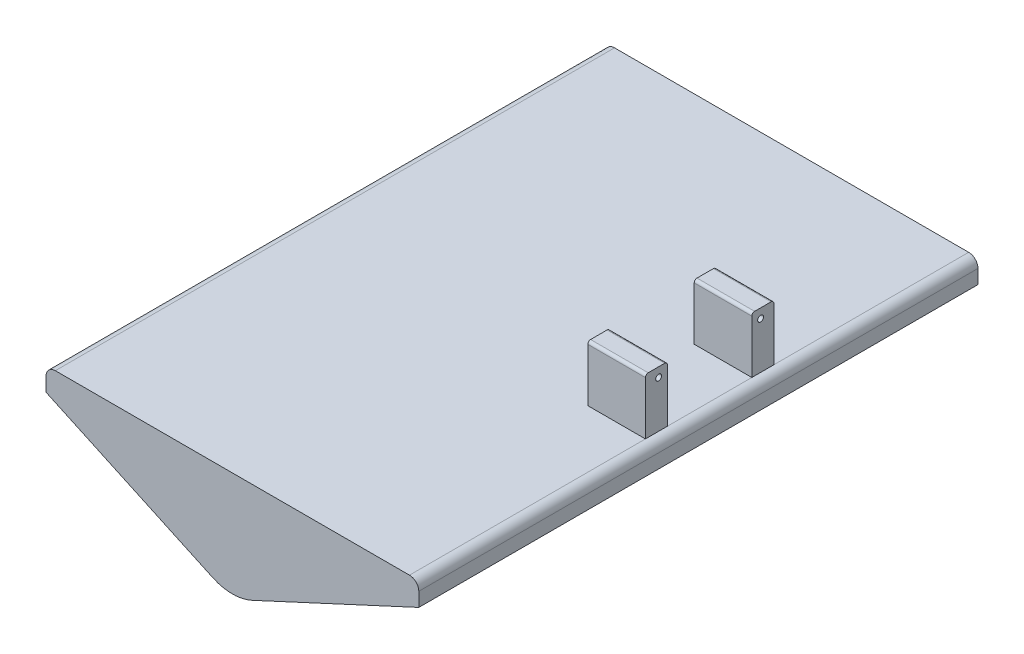
SolidWorks part; units mm, degrees
ref_plane "Front Plane" through (0, 0, 0) normal (0, 0, 1) x (1, 0, 0)
ref_plane "Top Plane" through (0, 0, 0) normal (0, 1, 0) x (1, 0, 0)
ref_plane "Right Plane" through (0, 0, 0) normal (1, 0, 0) x (0, 0, -1)
sketch "Sketch2" plane through (0, 0, 0) normal (0, 0, 1) x (1, 0, 0)
  line L0 (-50.8, -3.175) -> (-5.3359, -24.2247)
  line L1 (-50.8, 3.175) -> (50.8, 3.175)
  line L2 (-50.8, 3.175) -> (-50.8, -3.175)
  line L3 (-50.8, -3.175) -> (50.8, -3.175)
  line L4 (50.8, 3.175) -> (50.8, -3.175)
  line L5 (-50.8, 3.175) -> (50.8, -3.175) construction
  line L6 (-50.8, -3.175) -> (50.8, 3.175) construction
  line L7 (50.8, -3.175) -> (5.3359, -24.2247)
  arc A0 (-5.3359, -24.2247) -> (5.3359, -24.2247) centre (0, -12.7) ccw
  point P0 (0, 0)
  dimension "D3" = 25.4
  dimension "D1" = 101.6
  dimension "D2" = 6.35
  dimension "D4" = 12.7
extrude "Boss-Extrude1" add sketch "Sketch2" along normal blind 152.4 contours L0 A0 L7 L3 | L4 L1 L2 L3
sketch "Sketch3" plane through (0, 0, 152.4) normal (0, 0, 1) x (1, 0, 0)
  arc A0 (-5.3359, -24.2247) -> (5.3359, -24.2247) centre (0, -12.7) ccw construction
  arc A1 (-5.3359, -24.2247) -> (5.3359, -24.2247) centre (0, -12.7) ccw
  circle A2 centre (0, -12.7) radius 6.985
  dimension "D1" = 13.97
extrude "Cut-Extrude1" cut sketch "Sketch3" against normal through all from offset 6.35 contours A2 offset against normal yes
sketch "Sketch4" plane through (0, 3.175, 0) normal (0, 1, 0) x (1, 0, 0)
  line L0 (-50.8, -152.4) -> (-50.8, 0) construction
  line L1 (-50.8, -57.15) -> (50.8, -57.15)
  line L2 (-50.8, -57.15) -> (-50.8, -95.25)
  line L3 (-50.8, -95.25) -> (50.8, -95.25)
  line L4 (50.8, -57.15) -> (50.8, -95.25)
  line L5 (50.8, -152.4) -> (50.8, 0) construction
  line L6 (0, 0) -> (0, -152.4) construction
  line L7 (-50.8, 0) -> (50.8, 0) construction
  line L8 (-50.8, -152.4) -> (50.8, -152.4) construction
  line L9 (50.8, -76.2) -> (-50.8, -76.2) construction
  point P16 (0, -76.2)
  dimension "D1" = 38.1
extrude "Cut-Extrude2" cut sketch "Sketch4" against normal through all from offset 6.35 offset against normal yes
fillet "Fillet4" radius 2.54 2 edges at (-50.8, 3.175, 76.2) (50.8, 3.175, 76.2)
sketch "Sketch5" plane through (0, 3.175, 0) normal (0, 1, 0) x (1, 0, 0)
  line L0 (48.26, -152.4) -> (48.26, 0) construction
  line L1 (48.26, -82.1) -> (32.56, -82.1)
  line L2 (48.26, -82.1) -> (48.26, -88.1)
  line L3 (48.26, -88.1) -> (32.56, -88.1)
  line L4 (32.56, -82.1) -> (32.56, -88.1)
  line L5 (48.26, -53.1) -> (32.56, -53.1)
  line L6 (48.26, -53.1) -> (48.26, -59.1)
  line L7 (48.26, -59.1) -> (32.56, -59.1)
  line L8 (32.56, -53.1) -> (32.56, -59.1)
  line L9 (-48.26, -152.4) -> (48.26, -152.4) construction
  dimension "D1" = 15.7
  dimension "D2" = 6
  dimension "D3" = 15.7
  dimension "D4" = 6
  dimension "D5" = 23
  dimension "D6" = 64.3
extrude "Boss-Extrude2" add sketch "Sketch5" along normal blind 15.24
sketch "Sketch6" plane through (32.56, 0, 0) normal (-1, 0, 0) x (0, 0, 1)
  line L0 (82.1, 18.415) -> (82.1, 3.175) construction
  line L2 (82.1, 3.175) -> (88.1, 3.175) construction
  line L3 (59.1, 10.795) -> (82.1, 10.795) construction
  line L4 (59.1, 18.415) -> (59.1, 3.175) construction
  line L5 (70.6, 10.795) -> (70.6, 3.175) construction
  line L6 (0, 3.175) -> (152.4, 3.175) construction
  circle A0 centre (84.495, 15.875) radius 0.8
  circle A1 centre (56.705, 15.875) radius 0.8
  dimension "D1" = 1.6
  dimension "D2" = 12.7
  dimension "D3" = 2.395
extrude "Cut-Extrude4" cut sketch "Sketch6" against normal through all contours A1 | A0
fillet "Fillet7" radius 0.762 2 edges at (40.41, 18.415, 88.1) (40.41, 18.415, 82.1)
fillet "Fillet8" radius 0.762 2 edges at (40.41, 18.415, 53.1) (40.41, 18.415, 59.1)
sketch "Sketch18" plane through (32.56, 0, 0) normal (-1, 0, 0) x (0, 0, 1)
  point P0 (84.495, 15.875)
  point P3 (56.705, 15.875)
hole_wizard "Tap Drill for M2 Tap3" positions "Sketch18" profile "Sketch19" hole size "M2" standard "ISO" end condition through all
sketch "Sketch19" plane through (32.56, 15.875, 84.495) normal (0, 1, 0) x (0, 0, 1)
  line L0 (0, 0) -> (0, 18.24)
  line L1 (0, 18.24) -> (0.8, 18.24)
  line L2 (0.8, 18.24) -> (0.8, 0)
  line L5 (0.8, 0) -> (0, 0)
  line L11 (0, -6.35) -> (0, 107.95) construction
  dimension "Thru Hole Dia." = 1.6
  dimension "Thru Hole Depth" = 18.24
